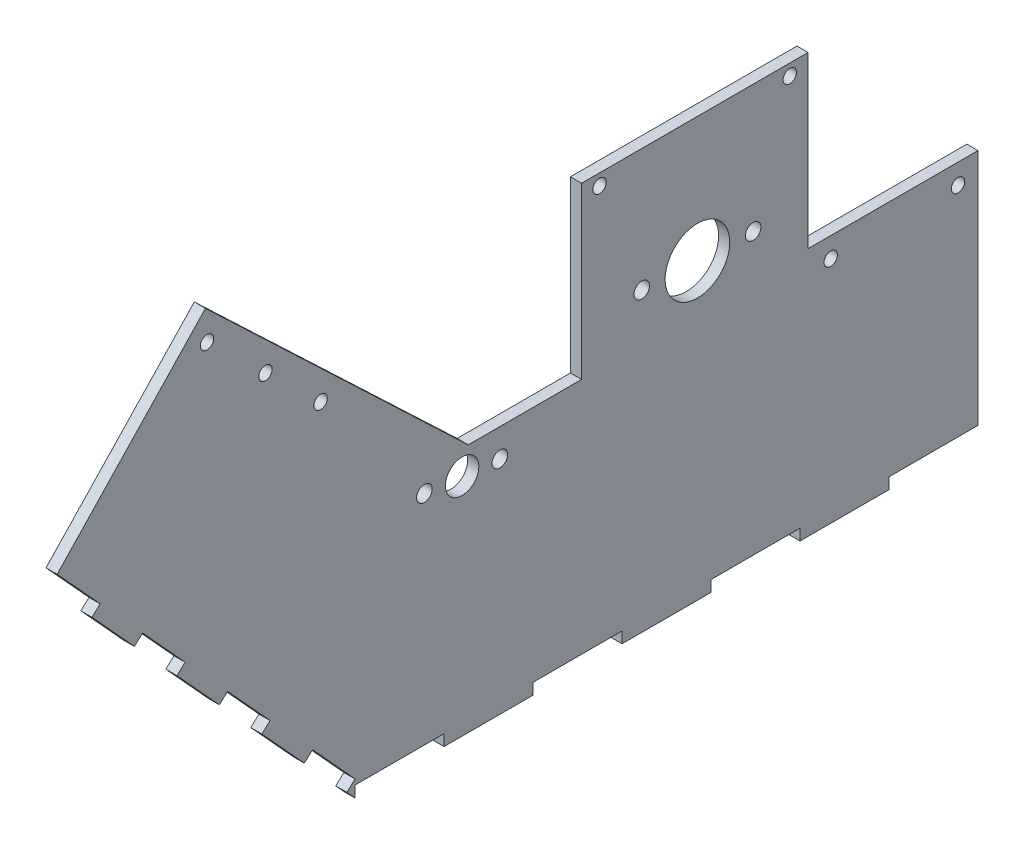
SolidWorks part; units mm, degrees
ref_plane "Front Plane" through (0, 0, 0) normal (0, 0, 1) x (1, 0, 0)
ref_plane "Top Plane" through (0, 0, 0) normal (0, 1, 0) x (1, 0, 0)
ref_plane "Right Plane" through (0, 0, 0) normal (1, 0, 0) x (0, 0, -1)
sketch "Sketch1" plane through (0, 0, 0) normal (1, 0, 0) x (0, 0, -1)
  line L0 (0, 0) -> (25.4, 0)
  line L1 (25.4, 0) -> (25.4, 38.1)
  line L2 (25.4, 38.1) -> (76.2, 38.1)
  line L3 (76.2, 38.1) -> (76.2, 0)
  line L4 (76.2, 0) -> (114.3, 0)
  line L5 (114.3, 0) -> (114.3, -55.88)
  line L6 (114.3, -55.88) -> (-25.4, -55.88)
  line L7 (0, 0) -> (-58.9362, 55.9729)
  line L8 (-25.4, -55.88) -> (-93.9192, 19.1378)
  line L9 (-93.9192, 19.1378) -> (-58.9362, 55.9729)
  circle A13 centre (-9.8409, -4.5239) radius 1.75
  circle A14 centre (-1.3863, -5.4011) radius 3.75
  circle A15 centre (7.0684, -6.2784) radius 1.75
  circle A16 centre (51.3905, 10.062) radius 7.25
  circle A17 centre (38.9028, 10.6165) radius 1.75
  circle A18 centre (63.8782, 9.5076) radius 1.75
  dimension "D1" = 25.4
  dimension "D2" = 50.8
  dimension "D3" = 38.1
  dimension "D4" = 38.1
  dimension "D5" = 55.88
  dimension "D6" = 139.7
  dimension "D7" = 81.28
  dimension "D8" = 101.6
  dimension "D9" = 50.8
extrude "Boss-Extrude1" add sketch "Sketch1" along normal blind 2.5
sketch "Sketch2" plane through (0, 0, 0) normal (-1, 0, 0) x (0, 0, 1)
  line L0 (-76.2, 35.5541) -> (-25.4, 35.5541) construction
  line L1 (-76.2, 0) -> (-76.2, 38.1) construction
  line L2 (-25.4, 38.1) -> (-25.4, 0) construction
  line L3 (62.1355, 52.6042) -> (4.0985, -2.8115) construction
  line L4 (58.9362, 55.9729) -> (93.9192, 19.1378) construction
  line L5 (-114.3, -4.4922) -> (-76.2, -4.4922) construction
  line L6 (-114.3, -55.88) -> (-114.3, 0) construction
  circle A0 centre (1.3863, -5.4011) radius 3.75 construction
  circle A1 centre (-72.0893, 35.5541) radius 1.5
  circle A2 centre (-29.4341, 35.5541) radius 1.5
  circle A3 centre (-109.8105, -4.4922) radius 1.5
  circle A4 centre (-81.28, -4.4922) radius 1.5
  circle A5 centre (58.5847, 49.2138) radius 1.5
  circle A6 centre (45.4813, 36.7023) radius 1.5
  circle A7 centre (33.117, 24.8964) radius 1.5
  dimension "D1" = 3
  dimension "D2" = 3
  dimension "D3" = 3
  dimension "D4" = 3
  dimension "D5" = 3
  dimension "D6" = 3
  dimension "D7" = 3
  dimension "D8" = 33.02
extrude "Cut-Extrude1" cut sketch "Sketch2" against normal blind 45.72
sketch "Sketch3" plane through (0, 0, 0) normal (-1, 0, 0) x (0, 0, 1)
  line L0 (-114.3, -53.38) -> (27.6834, -53.38) construction
  line L1 (-114.3, -55.88) -> (-114.3, 0) construction
  line L2 (93.9192, 19.1378) -> (25.4, -55.88) construction
  line L3 (25.4, -55.88) -> (-114.3, -55.88) construction
  line L4 (-94.3429, -55.88) -> (-74.3857, -55.88) construction
  line L5 (-114.3, -53.38) -> (-94.3429, -53.38)
  line L6 (-114.3, -53.38) -> (-114.3, -55.88)
  line L7 (-114.3, -55.88) -> (-94.3429, -55.88)
  line L8 (-94.3429, -53.38) -> (-94.3429, -55.88)
  line L9 (-74.3857, -53.38) -> (-54.4286, -53.38)
  line L10 (-74.3857, -53.38) -> (-74.3857, -55.88)
  line L11 (-74.3857, -55.88) -> (-54.4286, -55.88)
  line L12 (-54.4286, -53.38) -> (-54.4286, -55.88)
  line L13 (-34.4714, -53.38) -> (-14.5143, -53.38)
  line L14 (-34.4714, -53.38) -> (-34.4714, -55.88)
  line L15 (-34.4714, -55.88) -> (-14.5143, -55.88)
  line L16 (-14.5143, -53.38) -> (-14.5143, -55.88)
  line L17 (5.4429, -53.38) -> (25.4, -53.38)
  line L18 (5.4429, -53.38) -> (5.4429, -55.88)
  line L19 (5.4429, -55.88) -> (25.4, -55.88)
  line L20 (25.4, -53.38) -> (25.4, -55.88)
  line L21 (-54.4286, -55.88) -> (-34.4714, -55.88) construction
  line L22 (-14.5143, -55.88) -> (5.4429, -55.88) construction
  dimension "D1" = 2.5
extrude "Cut-Extrude2" cut sketch "Sketch3" against normal blind 2.54
sketch "Sketch4" plane through (0, 0, 0) normal (-1, 0, 0) x (0, 0, 1)
  line L0 (27.2329, -53.8732) -> (-29.3281, -2.2119) construction
  line L1 (93.9192, 19.1378) -> (25.4, -55.88) construction
  line L2 (25.387, -52.1872) -> (92.1933, 20.9552) construction
  line L3 (58.9362, 55.9729) -> (93.9192, 19.1378) construction
  line L4 (27.2329, -53.8732) -> (36.7595, -43.4431)
  line L5 (36.7595, -43.4431) -> (34.9136, -41.7571)
  line L6 (34.9136, -41.7571) -> (25.387, -52.1872)
  line L7 (25.387, -52.1872) -> (27.2329, -53.8732)
  line L8 (44.4402, -31.3269) -> (46.2862, -33.0129)
  line L9 (46.2862, -33.0129) -> (55.8128, -22.5828)
  line L10 (55.8128, -22.5828) -> (53.9669, -20.8968)
  line L11 (53.9669, -20.8968) -> (44.4402, -31.3269)
  line L12 (63.4935, -10.4666) -> (65.3394, -12.1526)
  line L13 (65.3394, -12.1526) -> (74.866, -1.7225)
  line L14 (74.866, -1.7225) -> (73.0201, -0.0365)
  line L15 (73.0201, -0.0365) -> (63.4935, -10.4666)
  line L16 (82.5467, 10.3937) -> (84.3926, 8.7077)
  line L17 (84.3926, 8.7077) -> (93.9192, 19.1378)
  line L18 (93.9192, 19.1378) -> (92.1933, 20.9552)
  line L19 (92.1933, 20.9552) -> (82.5467, 10.3937)
  line L20 (36.7595, -43.4431) -> (46.2862, -33.0129) construction
  line L21 (55.8128, -22.5828) -> (65.3394, -12.1526) construction
  line L22 (74.866, -1.7225) -> (84.3926, 8.7077) construction
  dimension "D1" = 99.06
  dimension "D2" = 2.5
extrude "Cut-Extrude3" cut sketch "Sketch4" against normal blind 2.54
